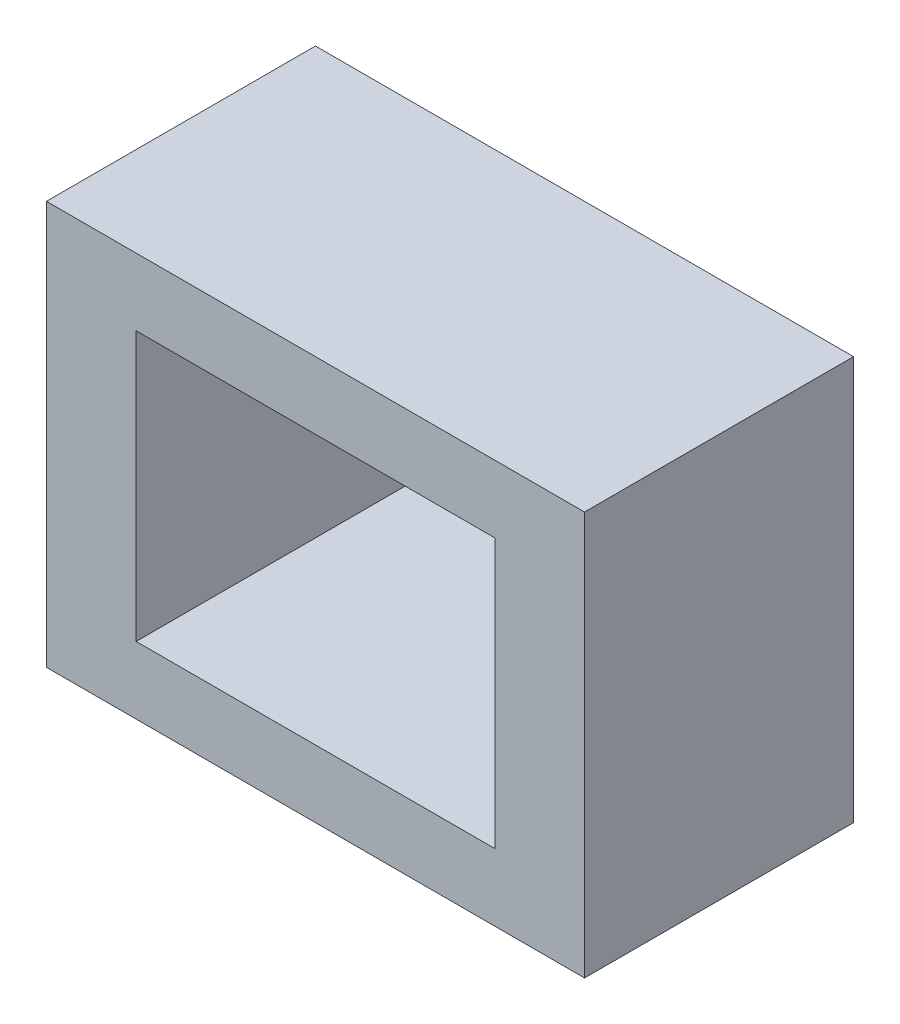
SolidWorks part; units mm, degrees
ref_plane "前视基准面" through (0, 0, 0) normal (0, 0, 1) x (1, 0, 0)
ref_plane "上视基准面" through (0, 0, 0) normal (0, 1, 0) x (1, 0, 0)
ref_plane "右视基准面" through (0, 0, 0) normal (1, 0, 0) x (0, 0, -1)
sketch "草图1" plane through (0, 0, 0) normal (0, 0, 1) x (1, 0, 0)
  line L1 (-200, -150) -> (200, -150)
  line L2 (-200, -150) -> (-200, 150)
  line L3 (-200, 150) -> (200, 150)
  line L4 (200, -150) -> (200, 150)
  line L5 (-200, -150) -> (200, 150) construction
  line L6 (-200, 150) -> (200, -150) construction
  line L7 (-300, 225) -> (300, 225)
  line L8 (-300, 225) -> (-300, -225)
  line L9 (-300, -225) -> (300, -225)
  line L10 (300, 225) -> (300, -225)
  line L11 (-300, 225) -> (300, -225) construction
  line L12 (-300, -225) -> (300, 225) construction
  point P0 (0, 0)
  point P6 (0, 0)
  dimension "D1" = 400
  dimension "D2" = 600
  dimension "D3" = 300
  dimension "D4" = 450
extrude "凸台-拉伸2" add sketch "草图1" along normal mid plane 300
